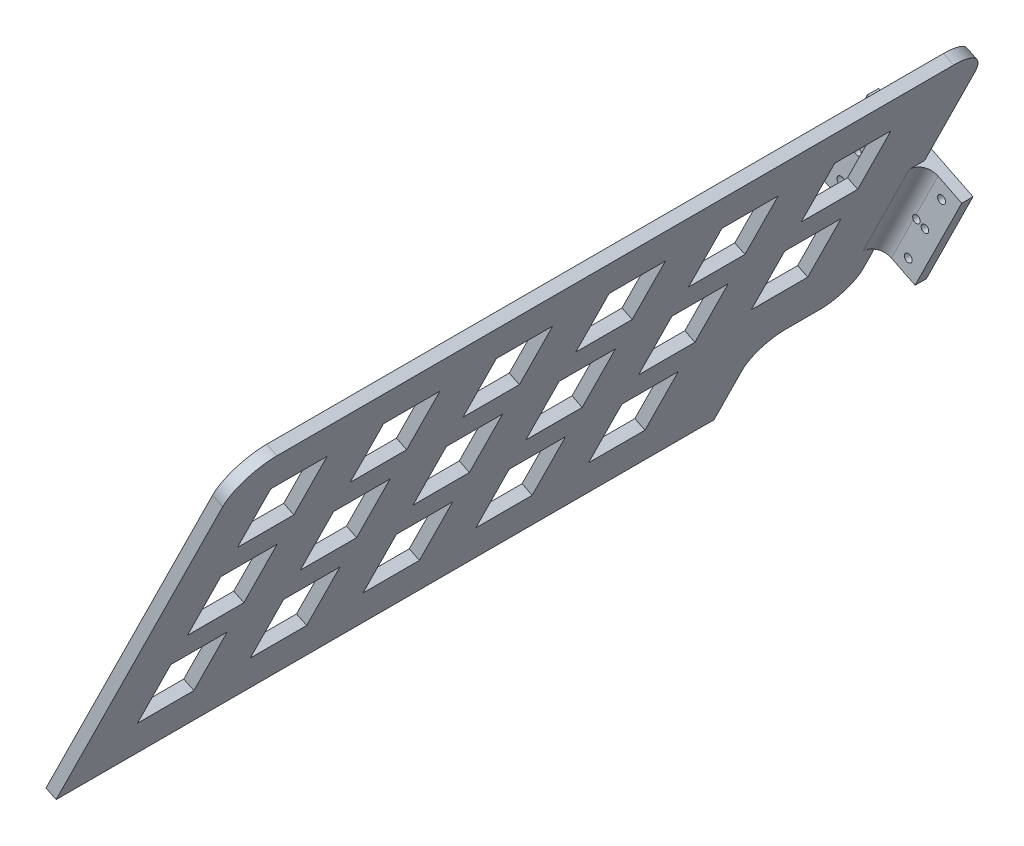
SolidWorks part; units mm, degrees
ref_plane "前视基准面" through (0, 0, 0) normal (0, 0, 1) x (1, 0, 0)
ref_plane "上视基准面" through (0, 0, 0) normal (0, 1, 0) x (1, 0, 0)
ref_plane "右视基准面" through (0, 0, 0) normal (1, 0, 0) x (0, 0, -1)
other "Configuration Table"
sketch "草图1" plane through (0, 0, 0) normal (0, 0, 1) x (1, 0, 0)
  line L0 (-68.5343, 4.2832) -> (-80.9444, -20.8165)
  line L1 (-68.5343, 4.2832) -> (-43.4347, -8.1269)
  line L2 (-80.9444, -20.8165) -> (-55.8447, -33.2265)
  line L3 (-43.4347, -8.1269) -> (-55.8447, -33.2265)
extrude "凸台-拉伸1" add sketch "草图1" along normal blind 3
sketch "草图2" plane through (0, 0, 3) normal (0, 0, 1) x (1, 0, 0)
  line L0 (-87.0384, -64.6567) -> (-51.5811, 7.0565) construction
  line L1 (-87.0384, -64.6567) -> (-38.2847, 33.949)
  line L2 (-87.0384, -64.6567) -> (-84.3491, -65.9863)
  line L3 (-38.2847, 33.949) -> (-35.5954, 32.6193)
  line L4 (-84.3491, -65.9863) -> (-35.5954, 32.6193)
  line L5 (-43.4347, -8.1269) -> (-68.5343, 4.2832) construction
  dimension "D1" = 110
  dimension "D2" = 3
  dimension "D3" = 40
extrude "凸台-拉伸2" add sketch "草图2" along normal blind 200
fillet "圆角1" radius 4 2 edges at (-62.2183, -14.4574, 3) (-59.529, -15.7871, 3)
sketch "草图4" plane through (-44.2521, 21.8796, 0) normal (-0.8964, 0.4432, 0) x (0, 0, 1)
  line L0 (3, -71.536) -> (28, -71.536)
  line L1 (3, -54.536) -> (3, -96.536) construction
  line L2 (28, -71.536) -> (28, -96.536)
  line L3 (203, -96.536) -> (3, -96.536) construction
  line L4 (3, -71.536) -> (3, -96.536)
  line L5 (3, -96.536) -> (28, -96.536)
  dimension "D1" = 25
  dimension "D2" = 25
extrude "切除-拉伸1" cut sketch "草图4" against normal blind 4
fillet "圆角3" radius 8 2 edges at (-74.6134, -42.9111, 3) (-74.6134, -42.9111, 28)
sketch "草图5" plane through (-41.5629, 20.55, 0) normal (0.8964, -0.4432, 0) x (0, 0, -1)
  line L0 (-68, -21.536) -> (-68, -1.536)
  line L1 (-38, -21.536) -> (-23, -21.536)
  line L2 (-38, -21.536) -> (-38, -1.536)
  line L3 (-38, -1.536) -> (-23, -1.536)
  line L4 (-23, -21.536) -> (-23, -1.536)
  line L5 (-68, -21.536) -> (-53, -21.536)
  line L6 (-53, -21.536) -> (-53, -1.536)
  line L7 (-68, -1.536) -> (-53, -1.536)
  line L8 (-98, -21.536) -> (-98, -1.536)
  line L9 (-98, -21.536) -> (-83, -21.536)
  line L10 (-83, -21.536) -> (-83, -1.536)
  line L11 (-98, -1.536) -> (-83, -1.536)
  line L12 (-128, -21.536) -> (-128, -1.536)
  line L13 (-128, -21.536) -> (-113, -21.536)
  line L14 (-113, -21.536) -> (-113, -1.536)
  line L15 (-128, -1.536) -> (-113, -1.536)
  line L16 (-158, -21.536) -> (-158, -1.536)
  line L17 (-158, -21.536) -> (-143, -21.536)
  line L18 (-143, -21.536) -> (-143, -1.536)
  line L19 (-158, -1.536) -> (-143, -1.536)
  line L20 (-188, -21.536) -> (-188, -1.536)
  line L21 (-188, -21.536) -> (-173, -21.536)
  line L22 (-173, -21.536) -> (-173, -1.536)
  line L23 (-188, -1.536) -> (-173, -1.536)
  line L24 (-68, -51.536) -> (-68, -31.536)
  line L25 (-68, -51.536) -> (-53, -51.536)
  line L26 (-53, -51.536) -> (-53, -31.536)
  line L27 (-68, -31.536) -> (-53, -31.536)
  line L28 (-98, -51.536) -> (-98, -31.536)
  line L29 (-98, -51.536) -> (-83, -51.536)
  line L30 (-83, -51.536) -> (-83, -31.536)
  line L31 (-98, -31.536) -> (-83, -31.536)
  line L32 (-128, -51.536) -> (-128, -31.536)
  line L33 (-128, -51.536) -> (-113, -51.536)
  line L34 (-113, -51.536) -> (-113, -31.536)
  line L35 (-128, -31.536) -> (-113, -31.536)
  line L36 (-158, -51.536) -> (-158, -31.536)
  line L37 (-158, -51.536) -> (-143, -51.536)
  line L38 (-143, -51.536) -> (-143, -31.536)
  line L39 (-158, -31.536) -> (-143, -31.536)
  line L40 (-188, -51.536) -> (-188, -31.536)
  line L41 (-188, -51.536) -> (-173, -51.536)
  line L42 (-173, -51.536) -> (-173, -31.536)
  line L43 (-188, -31.536) -> (-173, -31.536)
  line L44 (-68, -81.536) -> (-68, -61.536)
  line L45 (-68, -81.536) -> (-53, -81.536)
  line L46 (-53, -81.536) -> (-53, -61.536)
  line L47 (-68, -61.536) -> (-53, -61.536)
  line L48 (-98, -81.536) -> (-98, -61.536)
  line L49 (-98, -81.536) -> (-83, -81.536)
  line L50 (-83, -81.536) -> (-83, -61.536)
  line L51 (-98, -61.536) -> (-83, -61.536)
  line L52 (-128, -81.536) -> (-128, -61.536)
  line L53 (-128, -81.536) -> (-113, -81.536)
  line L54 (-113, -81.536) -> (-113, -61.536)
  line L55 (-128, -61.536) -> (-113, -61.536)
  line L56 (-158, -81.536) -> (-158, -61.536)
  line L57 (-158, -81.536) -> (-143, -81.536)
  line L58 (-143, -81.536) -> (-143, -61.536)
  line L59 (-158, -61.536) -> (-143, -61.536)
  line L60 (-188, -81.536) -> (-188, -61.536)
  line L61 (-188, -81.536) -> (-173, -81.536)
  line L62 (-173, -81.536) -> (-173, -61.536)
  line L63 (-188, -61.536) -> (-173, -61.536)
  line L64 (-38, -51.536) -> (-38, -31.536)
  line L65 (-38, -51.536) -> (-23, -51.536)
  line L66 (-23, -51.536) -> (-23, -31.536)
  line L67 (-38, -31.536) -> (-23, -31.536)
  line L72 (-23, -81.536) -> (-23, -61.536) [skipped]
  line L73 (-38, -81.536) -> (-38, -61.536) [skipped]
  line L74 (-38, -61.536) -> (-23, -61.536) [skipped]
  line L75 (-38, -81.536) -> (-23, -81.536) [skipped]
  line L76 (-203, 13.464) -> (-3, 13.464) construction
  line L78 (-203, -96.536) -> (-203, 13.464) construction
  dimension "D1" = 6
  dimension "D3" = 15
  dimension "D4" = 15
  dimension "D5" = 20
  dimension "D7" = 15
  dimension "D8" = 15
  dimension "D2" = 3
extrude "切除-拉伸2" cut sketch "草图5" against normal blind 10
fillet "圆角4" radius 10 1 edges at (-36.94, 33.2841, 203)
fillet "圆角5" radius 10 1 edges at (-36.94, 33.2841, 3)
ref_plane "基准面1" through (-53.2163, 26.3118, 0) normal (-0.8964, 0.4432, 0) x (0, 0, 1)
ref_plane "基准面2" through (-47.2184, -95.5005, 0) normal (-0.4432, -0.8964, 0) x (-0.8964, 0.4432, 0)
sketch "草图7" plane through (0, 0, 0) normal (0, 0, -1) x (-1, 0, 0)
  line L0 (53.6797, -19.8226) -> (52.7711, -17.985) construction
  circle A0 centre (48.7932, -9.9397) radius 1.05
  circle A2 centre (66.7215, -1.0754) radius 1.05
  circle A3 centre (71.1537, -10.0395) radius 1
  circle A4 centre (68.9126, -11.1475) radius 1
  circle A5 centre (75.5858, -19.0037) radius 1.05
  circle A6 centre (57.6575, -27.868) radius 1.05
  circle A7 centre (53.2254, -18.9038) radius 1
  circle A8 centre (55.4664, -17.7958) radius 1
extrude "切除-拉伸3" cut sketch "草图7" against normal blind 5
